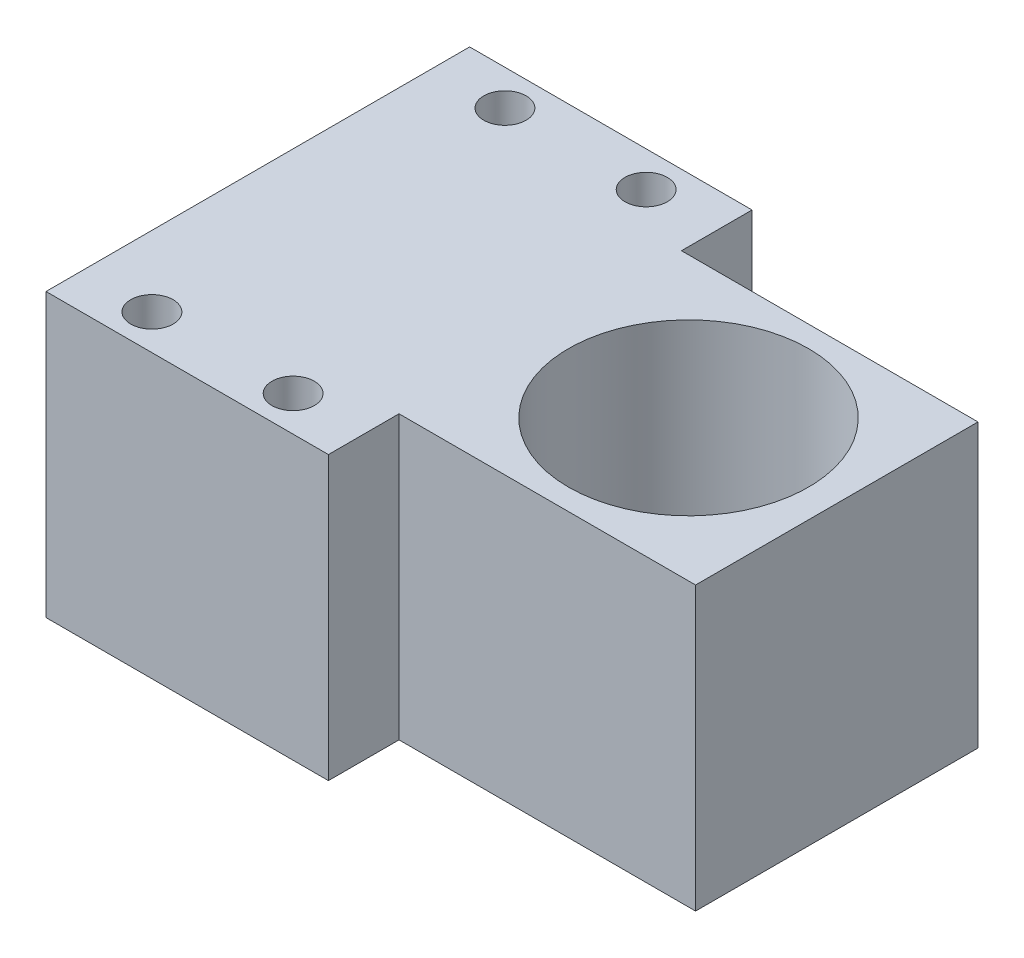
SolidWorks part; units mm, degrees
ref_plane "前视基准面" through (0, 0, 0) normal (0, 0, 1) x (1, 0, 0)
ref_plane "上视基准面" through (0, 0, 0) normal (0, 1, 0) x (1, 0, 0)
ref_plane "右视基准面" through (0, 0, 0) normal (1, 0, 0) x (0, 0, -1)
sketch "草图1" plane through (0, 0, 0) normal (1, 0, 0) x (0, 0, -1)
  line L1 (10, -10) -> (-10, -10)
  line L2 (10, -10) -> (10, 10)
  line L3 (10, 10) -> (-10, 10)
  line L4 (-10, -10) -> (-10, 10)
  line L5 (10, -10) -> (-10, 10) construction
  line L6 (10, 10) -> (-10, -10) construction
  circle A0 centre (0, 0) radius 7.5
  point P0 (0, 0)
  dimension "D1" = 20
  dimension "D2" = 20
extrude "凸台-拉伸1" add sketch "草图1" along normal blind 10
sketch "草图2" plane through (10, 0, 0) normal (1, 0, 0) x (0, 0, -1)
  line L0 (-10, 10) -> (-10, -10) construction
  line L1 (-10, 10) -> (-15, 10)
  line L2 (-10, 10) -> (-10, 8)
  line L3 (-10, 8) -> (-15, 8)
  line L4 (-15, 10) -> (-15, 8)
  line L6 (10, 10) -> (15, 10)
  line L7 (10, 10) -> (10, 8)
  line L8 (10, 8) -> (15, 8)
  line L9 (10, -8) -> (15, -8)
  line L10 (15, -10) -> (15, -8)
  line L11 (10, -10) -> (15, -10)
  line L12 (10, -10) -> (10, -8)
  line L13 (15, 10) -> (15, 8)
  line L14 (-10, -10) -> (-15, -10)
  line L15 (-10, -10) -> (-10, -8)
  line L16 (-10, -8) -> (-15, -8)
  line L17 (8, 10) -> (8, 15) [skipped]
  line L18 (10, 10) -> (10, 15) [skipped]
  line L19 (10, 15) -> (8, 15) [skipped]
  line L20 (10, 10) -> (8, 10) [skipped]
  line L21 (-10, -10) -> (-10, -15) [skipped]
  line L22 (-8, -10) -> (-8, -15) [skipped]
  line L23 (-10, -10) -> (-8, -10) [skipped]
  line L24 (-10, -15) -> (-8, -15) [skipped]
  line L25 (-15, -10) -> (-15, -8)
  point P23 (0, 0)
  dimension "D1" = 5
  dimension "D2" = 2
  dimension "D3" = 4
extrude "凸台-拉伸2" add sketch "草图2" along normal blind 0.0001 and the other way blind 10
sketch "草图3" plane through (0, -10, 0) normal (0, -1, 0) x (1, 0, 0)
  line L0 (5, -15) -> (5, -12.5) construction
  line L1 (0, -15) -> (10.0001, -15) construction
  circle A0 centre (5, -12.5) radius 1.5
  dimension "D1" = 2.5
extrude "切除-拉伸1" cut sketch "草图3" against normal through all
sketch "草图4" plane through (0, -10, 0) normal (0, -1, 0) x (1, 0, 0)
  line L0 (5, 15) -> (5, 12.5) construction
  line L1 (0, 15) -> (10.0001, 15) construction
  circle A0 centre (5, 12.5) radius 1.5
  dimension "D1" = 2.5
extrude "切除-拉伸2" cut sketch "草图4" against normal through all
sketch "草图5" plane through (10, 0, 0) normal (1, 0, 0) x (0, 0, -1)
  line L1 (-10, 10) -> (10, 10)
  line L2 (-10, 10) -> (-10, -10)
  line L3 (-10, -10) -> (10, -10)
  line L4 (10, 10) -> (10, -10)
extrude "凸台-拉伸3" add sketch "草图5" along normal blind 21
sketch "草图6" plane through (0, 10, 0) normal (0, 1, 0) x (1, 0, 0)
  line L0 (31, 10) -> (10.0001, -10) construction
  circle A0 centre (20.5, 0) radius 8.5
  dimension "D1" = 17
extrude "切除-拉伸3" cut sketch "草图6" against normal through all
sketch "草图7" plane through (0, 0, -10) normal (0, 0, -1) x (-1, 0, 0)
  line L1 (-10.0001, 8) -> (0, 8)
  line L2 (-10.0001, 8) -> (-10.0001, -8)
  line L3 (-10.0001, -8) -> (0, -8)
  line L4 (0, 8) -> (0, -8)
extrude "凸台-拉伸4" add sketch "草图7" along normal blind 5
sketch "草图8" plane through (0, 0, 10) normal (0, 0, 1) x (1, 0, 0)
  line L0 (10.0001, -10) -> (10.0001, -8) construction
  line L1 (0, 8) -> (10.0001, 8)
  line L2 (0, 8) -> (0, -9)
  line L3 (0, -9) -> (10.0001, -9)
  line L4 (10.0001, 8) -> (10.0001, -9)
extrude "凸台-拉伸5" add sketch "草图8" along normal blind 5
sketch "草图9" plane through (0, 10, 0) normal (0, 1, 0) x (1, 0, 0)
  circle A0 centre (5, -12.5) radius 1.5
  circle A1 centre (5, 12.5) radius 1.5
extrude "切除-拉伸4" cut sketch "草图9" against normal through all
sketch "草图10" plane through (0, 0, 0) normal (-1, 0, 0) x (0, 0, 1)
  line L1 (-15, -10) -> (15, -10)
  line L2 (-15, -10) -> (-15, 10)
  line L3 (-15, 10) -> (15, 10)
  line L4 (15, -10) -> (15, 10)
extrude "凸台-拉伸6" add sketch "草图10" along normal blind 10
sketch "草图11" plane through (-10, 0, 0) normal (-1, 0, 0) x (0, 0, 1)
  circle A0 centre (0, 0) radius 7.5
extrude "切除-拉伸5" cut sketch "草图11" against normal blind 10
sketch "草图12" plane through (0, -10, 0) normal (0, -1, 0) x (1, 0, 0)
  line L0 (5, -12.5) -> (-4.9999, -12.5) construction
  line L1 (5, 12.5) -> (-4.9999, 12.5) construction
  circle A0 centre (-4.9999, -12.5) radius 1.5
  circle A1 centre (-4.9999, 12.5) radius 1.5
  dimension "D1" = 10
  dimension "D2" = 10
extrude "切除-拉伸6" cut sketch "草图12" against normal blind 20
